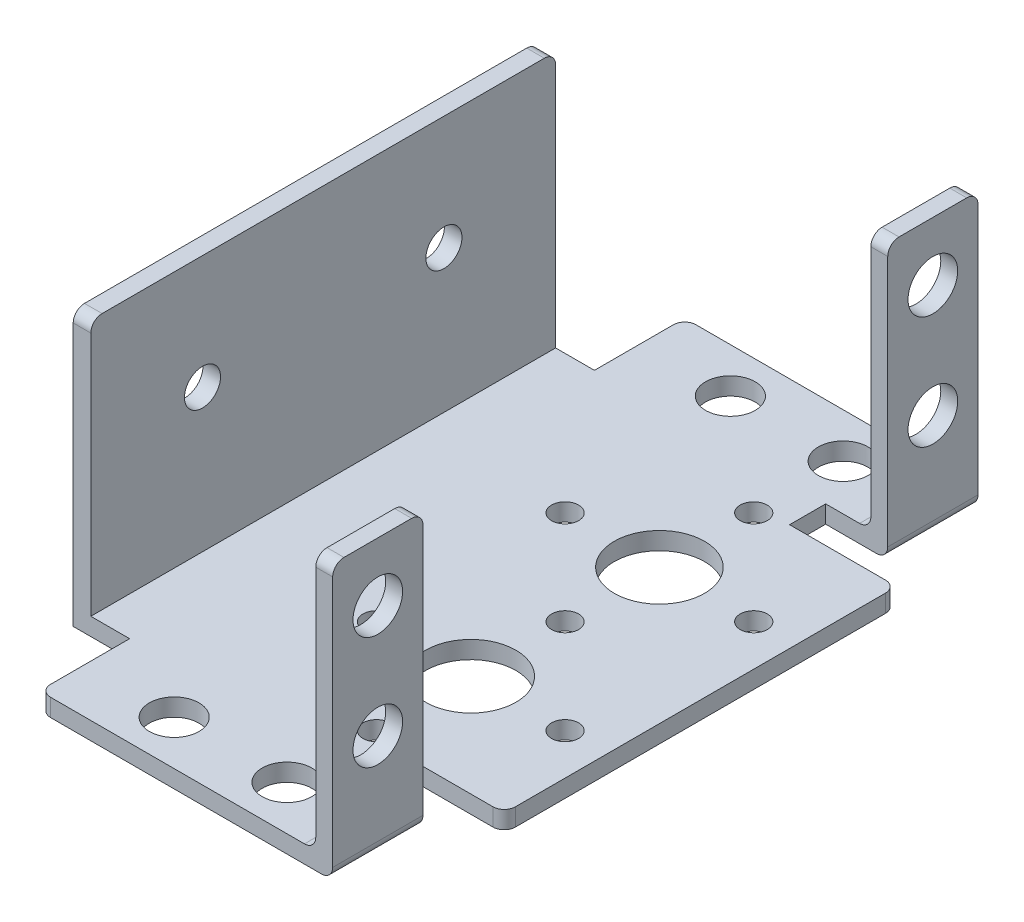
SolidWorks part; units mm, degrees
ref_plane "Front" through (0, 0, 0) normal (0, 0, 1) x (1, 0, 0)
ref_plane "Top" through (0, 0, 0) normal (0, 1, 0) x (1, 0, 0)
ref_plane "Right" through (0, 0, 0) normal (1, 0, 0) x (0, 0, -1)
sketch "Sketch1" plane through (0, 0, 0) normal (0, 0, 1) x (1, 0, 0)
  line L0 (0, 24.3) -> (1.56, 24.3)
  line L1 (35, 1.56) -> (35, 0)
  line L2 (1.56, 1.56) -> (35, 1.56)
  line L3 (1.56, 1.56) -> (1.56, 24.3)
  line L4 (0, 0) -> (35, 0)
  line L5 (0, 0) -> (0, 24.3)
  dimension "D1" = 1.56
  dimension "D2" = 1.56
  dimension "D3" = 35
  dimension "D4" = 24.3
extrude "Boss-Extrude1" add sketch "Sketch1" against normal blind 57.2
sketch "Sketch2" plane through (0, 0, 0) normal (0, -1, 0) x (1, 0, 0)
  line L0 (35, -28.6) -> (0, -28.6) construction
  line L1 (35, -57.2) -> (35, 0) construction
  line L2 (0, -57.2) -> (0, 0) construction
  line L3 (23, -28.6) -> (23, -3.95) construction
  line L5 (0, -57.2) -> (0, 0) construction
  line L6 (13, -3.95) -> (23, -3.95) construction
  line L7 (35, 0) -> (1.56, 0) construction
  line L8 (13, -1.75) -> (23, -1.75) construction
  line L9 (30.16, -19.04) -> (32.56, -19.04) construction
  line L11 (21.8, -13.08) -> (24.2, -13.08) construction
  line L12 (21.8, -13.08) -> (21.8, -10.68) construction
  line L13 (21.8, -10.68) -> (24.2, -10.68) construction
  line L14 (20.8, -6.15) -> (25.2, -6.15) construction
  line L15 (20.8, -6.15) -> (20.8, -1.75) construction
  line L16 (20.8, -1.75) -> (25.2, -1.75) construction
  line L17 (25.2, -6.15) -> (25.2, -1.75) construction
  line L18 (10.8, -6.15) -> (15.2, -6.15) construction
  line L19 (10.8, -6.15) -> (10.8, -1.75) construction
  line L20 (10.8, -1.75) -> (15.2, -1.75) construction
  line L21 (15.2, -6.15) -> (15.2, -1.75) construction
  line L22 (19, -24.24) -> (27, -24.24) construction
  line L23 (19, -24.24) -> (19, -16.24) construction
  line L24 (19, -16.24) -> (27, -16.24) construction
  line L25 (27, -24.24) -> (27, -16.24) construction
  line L26 (30.16, -19.04) -> (30.16, -21.44) construction
  line L27 (30.16, -21.44) -> (32.56, -21.44) construction
  line L28 (32.56, -19.04) -> (32.56, -21.44) construction
  line L29 (24.2, -13.08) -> (24.2, -10.68) construction
  circle A0 centre (23, -20.24) radius 4
  circle A1 centre (13, -53.25) radius 2.2
  circle A2 centre (23, -28.6) radius 1.2
  circle A3 centre (14.64, -20.24) radius 1.2
  circle A4 centre (23, -11.88) radius 1.2
  circle A5 centre (31.36, -20.24) radius 1.2
  circle A6 centre (23, -53.25) radius 2.2
  circle A7 centre (14.64, -36.96) radius 1.2
  circle A8 centre (31.36, -36.96) radius 1.2
  circle A9 centre (23, -3.95) radius 2.2
  circle A10 centre (23, -45.32) radius 1.2
  circle A11 centre (23, -36.96) radius 4
  circle A12 centre (13, -3.95) radius 2.2
  point P15 (23, -20.24)
  dimension "D1" = 8
  dimension "D3" = 2.4
  dimension "D4" = 4.4
  dimension "D5" = 10
  dimension "D7" = 3.95
  dimension "D6" = 13
  dimension "D8" = 3.16
  dimension "D2" = 4
extrude "Cut-Extrude1" cut sketch "Sketch2" against normal through all
sketch "Sketch3" plane through (0, 0, 0) normal (-1, 0, 0) x (0, 0, 1)
  line L0 (0, 1.56) -> (0, 24.3) construction
  line L2 (-8, 24.3) -> (-8, 0)
  line L3 (-28.6, 24.3) -> (-28.6, 0) construction
  line L4 (-57.2, 24.3) -> (0, 24.3) construction
  line L5 (-57.2, 0) -> (0, 0) construction
  line L6 (-8, 24.3) -> (0, 24.3)
  line L7 (0, 24.3) -> (0, 0)
  line L8 (0, 0) -> (-8, 0)
  line L9 (-57.2, 0) -> (-49.2, 0)
  line L10 (-57.2, 24.3) -> (-57.2, 0)
  line L11 (-49.2, 24.3) -> (-57.2, 24.3)
  line L12 (-49.2, 24.3) -> (-49.2, 0)
  circle A0 centre (-17.9, 14.2) radius 1.6
  circle A1 centre (-39.3, 14.2) radius 1.6
  dimension "D1" = 8
  dimension "D2" = 9.9
  dimension "D3" = 10.1
  dimension "D5" = 3.2
  dimension "D4" = 24.3
extrude "Cut-Extrude3" cut sketch "Sketch3" against normal blind 5
sketch "Sketch4" plane through (0, 1.56, 0) normal (0, 1, 0) x (1, 0, 0)
  line L0 (35, 28.6) -> (0, 28.6) construction
  line L1 (35, 57.2) -> (35, 0) construction
  line L2 (0, 49.2) -> (0, 8) construction
  line L3 (35, 57.2) -> (31, 57.2)
  line L4 (35, 0) -> (5, 0) construction
  line L5 (35, 46) -> (35, 57.2)
  line L7 (31, 8) -> (31, 0)
  line L8 (25.5, 11.2) -> (35, 11.2)
  line L9 (25.5, 8) -> (25.5, 11.2)
  line L10 (31, 8) -> (25.5, 8)
  line L11 (31, 49.2) -> (25.5, 49.2)
  line L12 (25.5, 49.2) -> (25.5, 46)
  line L13 (35, 11.2) -> (35, 0)
  line L14 (35, 0) -> (31, 0)
  line L15 (25.5, 46) -> (35, 46)
  line L16 (31, 49.2) -> (31, 57.2)
  dimension "D1" = 9.5
  dimension "D2" = 3.2
  dimension "D3" = 4
  dimension "D4" = 8
extrude "Cut-Extrude4" cut sketch "Sketch4" against normal through all
sketch "Sketch5" plane through (0, 1.56, 0) normal (0, 1, 0) x (1, 0, 0)
  line L0 (35, 28.6) -> (0, 28.6) construction
  line L1 (35, 46) -> (35, 11.2) construction
  line L2 (0, 49.2) -> (0, 8) construction
  line L3 (31, 57.2) -> (31, 49.2)
  line L5 (31, 49.2) -> (29.5, 49.2)
  line L6 (29.5, 49.2) -> (29.5, 57.2)
  line L7 (29.5, 57.2) -> (31, 57.2)
  line L8 (29.5, 0) -> (31, 0)
  line L9 (29.5, 8) -> (29.5, 0)
  line L10 (31, 8) -> (29.5, 8)
  line L11 (31, 0) -> (31, 8)
  dimension "D1" = 1.5
  dimension "D2" = 8
extrude "Boss-Extrude2" add sketch "Sketch5" along normal up to surface (22.74 mm away) up to face at (0.78, 24.3, -28.6)
fillet "Fillet1" radius 1 4 edges at (31, 0, -4) (29.5, 1.56, -4) (29.5, 1.56, -53.2) (31, 0, -53.2)
sketch "Sketch6" plane through (31, 0, 0) normal (1, 0, 0) x (0, 0, -1)
  line L0 (0, 1) -> (0, 24.3) construction
  line L2 (4, 9.1) -> (4, 19.1) construction
  line L3 (0, 24.3) -> (8, 24.3) construction
  line L5 (28.6, 24.3) -> (28.6, 0) construction
  line L6 (49.2, 24.3) -> (8, 24.3) construction
  line L7 (46, 0) -> (11.2, 0) construction
  circle A0 centre (4, 19.1) radius 2.2
  circle A1 centre (4, 9.1) radius 2.2
  circle A2 centre (53.2, 9.1) radius 2.2
  circle A3 centre (53.2, 19.1) radius 2.2
  dimension "D1" = 10
  dimension "D2" = 4.4
  dimension "D3" = 4
  dimension "D4" = 5.2
extrude "Cut-Extrude5" cut sketch "Sketch6" against normal blind 5
fillet "Fillet2" radius 1 10 edges at (35, 0.78, -11.2) (5, 0.78, 0) (0.78, 24.3, -8) (30.25, 24.3, 0) (5, 0.78, -57.2) (30.25, 24.3, -49.2) (30.25, 24.3, -57.2) (0.78, 24.3, -49.2) (30.25, 24.3, -8) (35, 0.78, -46)
